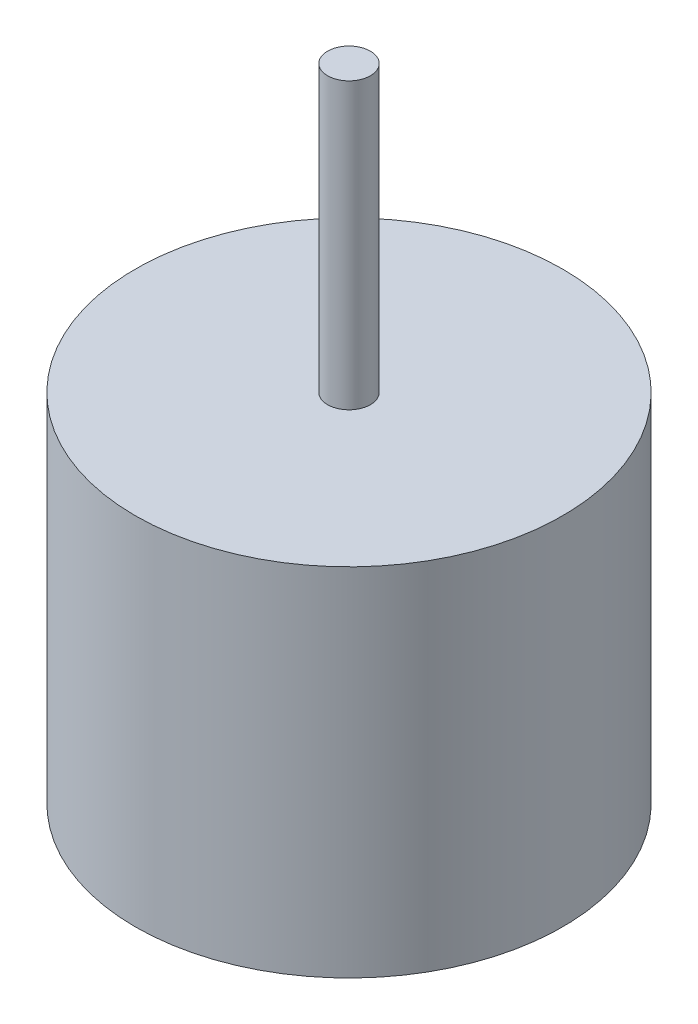
SolidWorks part; units mm, degrees
ref_plane "Plano frontal" through (0, 0, 0) normal (0, 0, 1) x (1, 0, 0)
ref_plane "Plano superior" through (0, 0, 0) normal (0, 1, 0) x (1, 0, 0)
ref_plane "Plano direito" through (0, 0, 0) normal (1, 0, 0) x (0, 0, -1)
sketch "Esboço1" plane through (0, 0, 0) normal (0, 1, 0) x (1, 0, 0)
  circle A0 centre (0, 0) radius 15
  circle A1 centre (0, 0) radius 1.5
  point P4 (0, 0)
  point P5 (0, 0)
  dimension "D1" = 30
  dimension "D2" = 3
extrude "Ressalto-extrusão1" add sketch "Esboço1" along normal blind 25
sketch "Esboço4" plane through (0, 25, 0) normal (0, 1, 0) x (1, 0, 0)
  circle A0 centre (0, 0) radius 1.5
extrude "Ressalto-extrusão2" add sketch "Esboço4" along normal blind 20 and the other way through all
